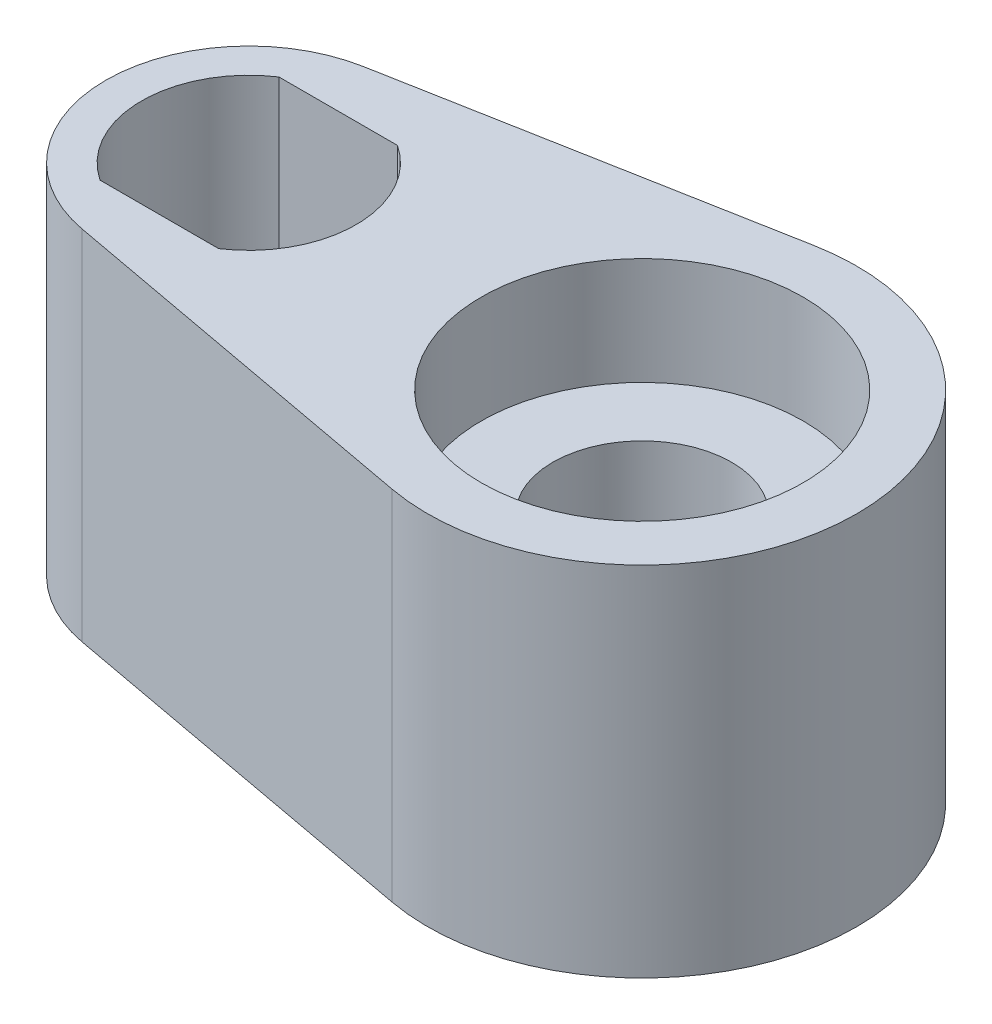
SolidWorks part; units mm, degrees
ref_plane "Спереди" through (0, 0, 0) normal (0, 0, 1) x (1, 0, 0)
ref_plane "Сверху" through (0, 0, 0) normal (0, 1, 0) x (1, 0, 0)
ref_plane "Справа" through (0, 0, 0) normal (1, 0, 0) x (0, 0, -1)
sketch "Эскиз1" plane through (0, 0, 0) normal (0, 1, 0) x (1, 0, 0)
  circle A0 centre (0, 0) radius 1.5
  circle A1 centre (0, 0) radius 1.1
  dimension "D1" = 3
  dimension "D2" = 2.2
extrude "Бобышка-Вытянуть1" add sketch "Эскиз1" along normal blind 6.5
sketch "Эскиз2" plane through (0, 6.5, 0) normal (0, 1, 0) x (1, 0, 0)
  circle A0 centre (0, 0) radius 4
  circle A1 centre (0, 0) radius 1.1 construction
  circle A2 centre (0, 0) radius 1.1
  dimension "D1" = 8
extrude "Бобышка-Вытянуть2" add sketch "Эскиз2" along normal blind 1
sketch "Эскиз3" plane through (0, 7.5, 0) normal (0, 1, 0) x (1, 0, 0)
  line L0 (-1.6583, 2.5) -> (1.6583, 2.5)
  line L1 (-1000, 0) -> (49000, 0) construction
  line L2 (-1.6583, -2.5) -> (1.6583, -2.5)
  circle A0 centre (0, 0) radius 3
  circle A1 centre (0, 0) radius 4
  circle A2 centre (0, 0) radius 4
  circle M6 centre (0, 0) radius 4
  dimension "D2" = 6
  dimension "D3" = 5
  dimension "D1" = 0
extrude "Бобышка-Вытянуть3" add sketch "Эскиз3" along normal blind 9 contours L1 A0 M6 | L0 A0 | L1 A2 A0 | L2 A0
sketch "Эскиз4" plane through (0, 6.5, 0) normal (0, -1, 0) x (1, 0, 0)
  line L0 (0, 0) -> (11, 0) construction
  line L1 (-0.7273, 3.9333) -> (9.9091, 5.9)
  line L2 (-0.7273, -3.9333) -> (9.9091, -5.9)
  circle A0 centre (11, 0) radius 2.5
  circle A1 centre (11, 0) radius 6
  circle A2 centre (0, 0) radius 4 construction
  circle A4 centre (0, 0) radius 4
  circle A5 centre (0, 0) radius 4
  dimension "D2" = 5
  dimension "D3" = 12
  dimension "D1" = 11
  dimension "D4" = 0
extrude "Бобышка-Вытянуть4" add sketch "Эскиз4" against normal up to surface (10 mm away)
sketch "Эскиз5" plane through (0, 16.5, 0) normal (0, 1, 0) x (1, 0, 0)
  circle A0 centre (11, 0) radius 4.5
  dimension "D1" = 9
extrude "Вырез-Вытянуть1" cut sketch "Эскиз5" against normal blind 3
sketch "Эскиз6" plane through (0, 0, 0) normal (0, -1, 0) x (1, 0, 0)
  circle A1 centre (0, 0) radius 1.5
  circle A2 centre (0, 0) radius 1.5
  dimension "D1" = 0
extrude "Вырез-Вытянуть3" cut sketch "Эскиз6" against normal up to surface (6.5 mm away) up to face at (0, 6.5, 1.5)
